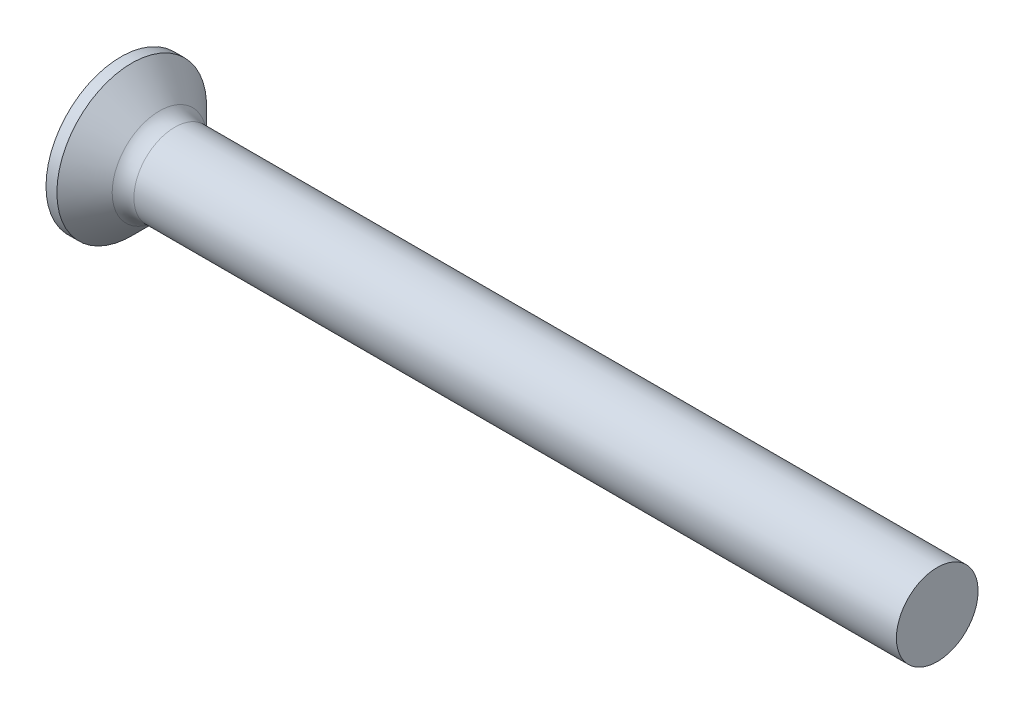
SolidWorks part; units mm, degrees
revolve "Base-Revolve" add sketch "BodySke" angle 360 about L5
sketch "BodySke" plane through (0, 0, 0) normal (0, 0, 1) x (1, 0, 0)
  line L0 (0, 0) -> (0, 2.75)
  line L1 (0, 2.75) -> (0.4, 2.75)
  line L2 (1.65, 1.5) -> (30, 1.5)
  line L3 (30, 1.5) -> (30, 0)
  line L4 (30, 0) -> (0, 0)
  line L5 (-6.35, 0) -> (82.55, 0) construction
  line L6 (1.65, -1.5) -> (30, -1.5) construction
  line L7 (0.4, -2.75) -> (1.65, -1.5) construction
  line L8 (0.4, 2.75) -> (1.65, 1.5)
  line L9 (0, -2.75) -> (0.4, -2.75) construction
  line L10 (2.15, 3.0875) -> (2.15, -6.4375) construction
  line L11 (0, 6.35) -> (0, -3.175) construction
  dimension "Diameter" = 3
  dimension "Length" = 30
  dimension "Head_ht" = 1.65
  dimension "Head_dia" = 5.5
  dimension "Head_ang" = 90
  dimension "D6" = 0.4
  dimension "Advance" = 0.5
  dimension "Thread_nom" = 30
cosmetic thread "ThreadCosmetic" [suppressed] parameters "Thread_length"=27.85, "Thread_minor"=2.439
ref_plane "Plane1" through (0, 0, 0) normal (0, 0, 1) x (1, 0, 0)
ref_plane "Plane2" through (0, 0, 0) normal (0, 1, 0) x (1, 0, 0)
ref_plane "Plane3" through (0, 0, 0) normal (1, 0, 0) x (0, 0, -1)
other "Configuration Table"
fillet "Fillet1" radius 0.8 1 edges at (1.65, 0, 1.5)
sketch "Sketch3" plane through (0, 0, 0) normal (-1, 0, 0) x (0, 0, 1)
  line L0 (-0.37, 1.5) -> (0.37, 1.5)
  line L1 (0.37, 1.5) -> (0.37, -1.5)
  line L2 (0.37, -1.5) -> (-0.37, -1.5)
  line L3 (-0.37, -1.5) -> (-0.37, 1.5)
  dimension "Cross_dia" = 3
  dimension "Cross_width" = 0.74
  dimension "D1" = 1.5
  dimension "D2" = 0.37
ref_plane "Plane4" through (2.01, 0, 0) normal (-1, 0, 0) x (0, 0, 1)
sketch "Sketch4" plane through (2.01, 0, 0) normal (-1, 0, 0) x (0, 0, 1)
  line L0 (-0.37, 0.4979) -> (0.37, 0.4979)
  line L3 (0.37, 0.4979) -> (0.37, -0.4979)
  line L4 (0.37, -0.4979) -> (-0.37, -0.4979)
  line L5 (-0.37, -0.4979) -> (-0.37, 0.4979)
  dimension "D2" = 0.9957
  dimension "D1" = 0.74
  dimension "D4" = 0.4979
  dimension "D3" = 0.37
loft "Recess" cut profiles "Sketch3", "Sketch4"
pattern_circular "RecPat" count 2 every 90 about axis through (0, 0, 0) along (1, 0, 0) of "Recess"
sketch "RecCorSke" plane through (0, 0, 0) normal (0, 0, 1) x (1, 0, 0)
  line L0 (-3.175, 0) -> (15.875, 0) construction
  line L2 (0, 0) -> (0, 0.6966)
  line L3 (0, 0.6966) -> (2.01, 0.556)
  line L4 (2.01, 0.556) -> (2.1907, 0)
  line L5 (2.1907, 0) -> (0, 0)
  dimension "Diameter" = 1.112
  dimension "Depth" = 2.01
  dimension "Draft_angle" = 4
  dimension "Bottom_angle" = 18
revolve "RecessCore" cut sketch "RecCorSke" angle 360 about L0
sketch "ThdSchSke" plane through (0, 0, 0) normal (0, 0, 1) x (1, 0, 0)
  line L0 (2.15, -1.2195) -> (1.9536, -1.5)
  line L1 (2.15, -1.2195) -> (2.3464, -1.5)
  line L2 (2.3464, -1.5) -> (2.3464, -1.875)
  line L3 (-3.175, 0) -> (5.1513, 0) construction
  line L5 (2.3464, -1.875) -> (1.9536, -1.875)
  line L6 (1.9536, -1.875) -> (1.9536, -1.5)
  line L7 (0, 2.75) -> (0, -2.75) construction
  dimension "Diameter" = 3
  dimension "Thread_minor" = 2.439
  dimension "Start" = 2.15
revolve "ThreadSchematic" [suppressed] cut sketch "ThdSchSke" angle 360 about L3
pattern_linear "ThdSchPat" [suppressed]
equation "\"D1@Sketch3\" = \"Cross_dia@Sketch3\" / 2"
equation "\"D2@Sketch3\" = \"Cross_width@Sketch3\" / 2"
equation "\"Depth@RecCorSke\" = \"Cross_depth@Plane4\""
equation "\"D1@Sketch4\" = \"Cross_width@Sketch3\""
equation "\"D2@Sketch4\" = \"Cross_dia@Sketch3\" - 2.0 * \"Cross_depth@Plane4\" * tan(26.5  * 0.017453292)"
equation "\"D3@Sketch4\" = \"D1@Sketch4\" / 2"
equation "\"D4@Sketch4\" = \"D2@Sketch4\" / 2"
equation "\"Thread_length@ThreadCosmetic\" = ((sgn( (\"Length@BodySke\" - \"Advance@BodySke\" * 1.0 - \"Head_ht@BodySke\" ) - \"Thread_nom@BodySke\" )-1)*( (\"Length@BodySke\" - \"Advance@BodySke\" * 1.0 - \"Head_ht@BodySke\" ) - \"Thread_nom@BodySke\" ))/-2+ \"Thread_nom@BodySke\""
equation "\"Thread_minor@ThdSchSke\" = \"Thread_minor@ThreadCosmetic\""
equation "\"Diameter@ThdSchSke\" = \"Diameter@BodySke\""
equation "\"Overcut@ThdSchSke\" = \"Diameter@BodySke\" * 1.25"
equation "\"Start@ThdSchSke\" = 0.000001 + \"Length@BodySke\" - \"Thread_length@ThreadCosmetic\"  '---Countersunk---"
equation "\"Num_threads@ThdSchPat\" = int( \"Thread_length@ThreadCosmetic\" / \"Advance@BodySke\" + 0.999 )  + 1"
equation "\"Advance@ThdSchPat\" = \"Thread_length@ThreadCosmetic\" /  (\"Num_threads@ThdSchPat\" - 1) 'relax it"
